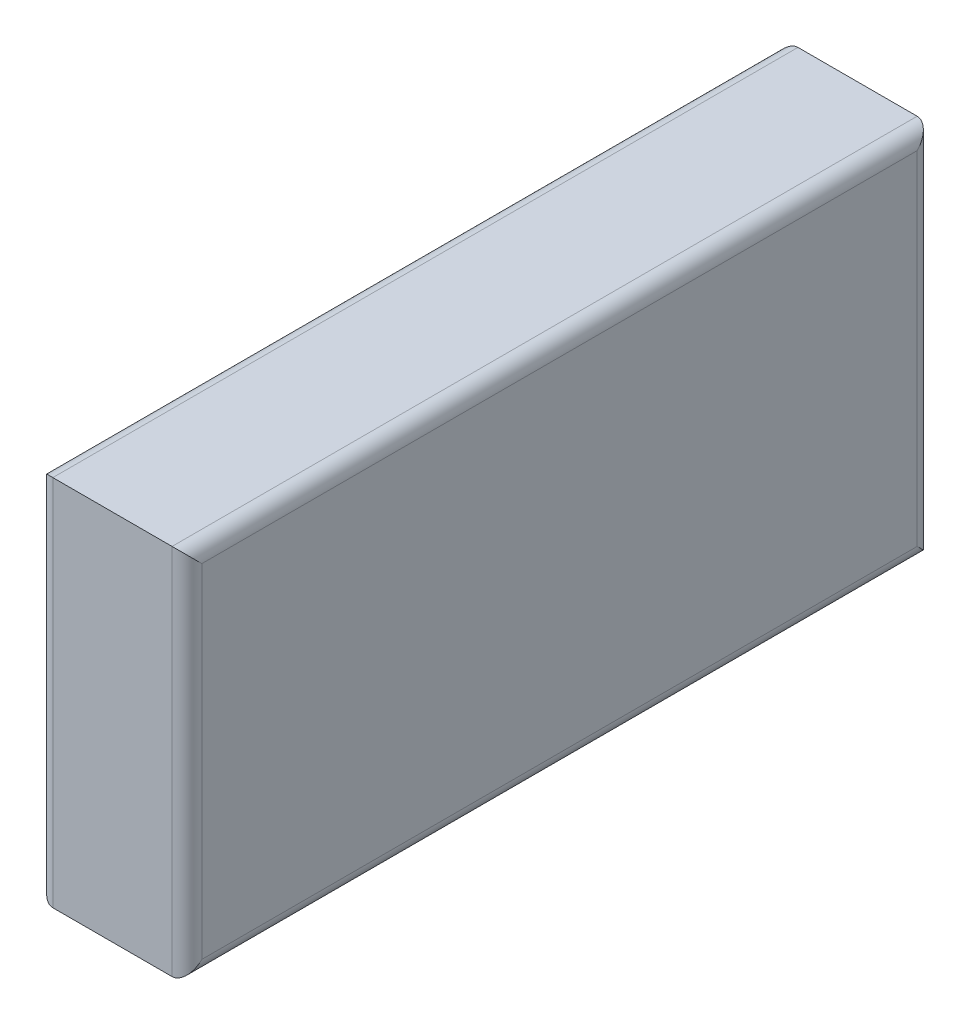
SolidWorks part; units mm, degrees
ref_plane "Alzado" through (0, 0, 0) normal (0, 0, 1) x (1, 0, 0)
ref_plane "Planta" through (0, 0, 0) normal (0, 1, 0) x (1, 0, 0)
ref_plane "Vista lateral" through (0, 0, 0) normal (1, 0, 0) x (0, 0, -1)
sketch "Croquis1" plane through (0, 0, 0) normal (0, 0, 1) x (1, 0, 0)
  line L1 (-30.1118, 8.0928) -> (-10.1118, 8.0928)
  line L2 (-30.1118, 8.0928) -> (-30.1118, -41.9072)
  line L3 (-30.1118, -41.9072) -> (-10.1118, -41.9072)
  line L4 (-10.1118, 8.0928) -> (-10.1118, -41.9072)
extrude "Saliente-Extruir1" add sketch "Croquis1" along normal blind 100
fillet "Redondeo1" radius 2 8 edges at (-10.1118, 8.0928, 50) (-30.1118, -16.9072, 0) (-10.1118, -16.9072, 0) (-30.1118, -16.9072, 100) (-10.1118, -16.9072, 100) (-30.1118, -41.9072, 50) (-10.1118, -41.9072, 50) (-30.1118, 8.0928, 50)
